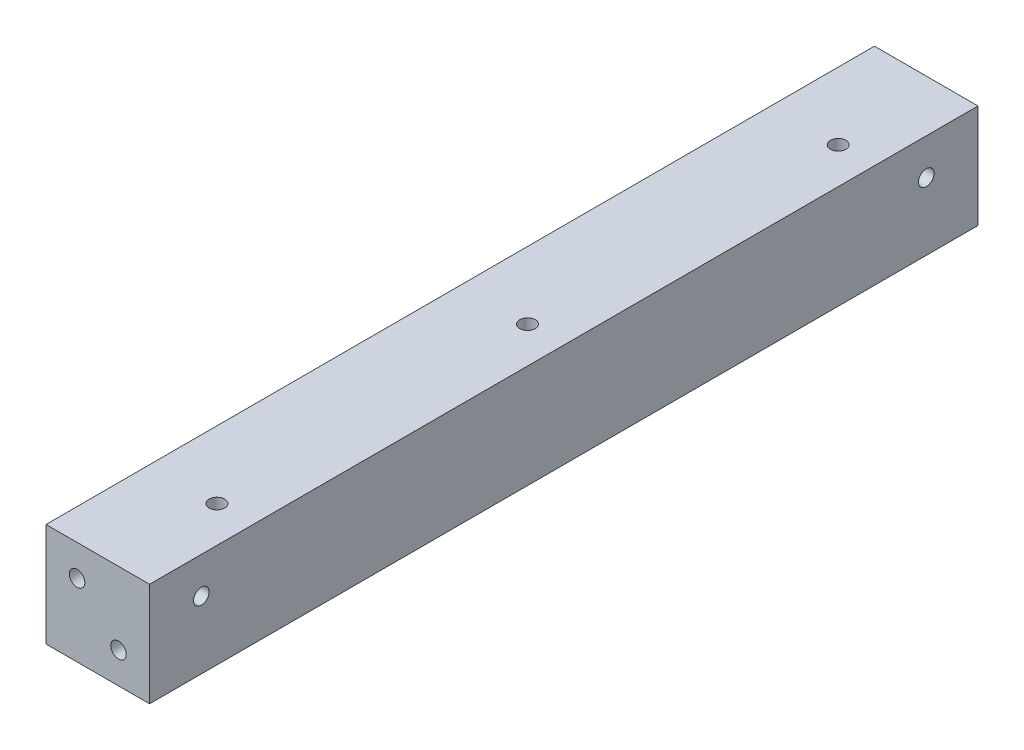
SolidWorks part; units mm, degrees
ref_plane "Ön Düzlem" through (0, 0, 0) normal (0, 0, 1) x (1, 0, 0)
ref_plane "Üst Düzlem" through (0, 0, 0) normal (0, 1, 0) x (1, 0, 0)
ref_plane "Sağ Düzlem" through (0, 0, 0) normal (1, 0, 0) x (0, 0, -1)
sketch "Çizim1" plane through (0, 0, 0) normal (0, 0, 1) x (1, 0, 0)
  line L0 (0, 20) -> (20, 0) construction
  line L1 (0, 0) -> (20, 0)
  line L2 (0, 0) -> (0, 20)
  line L3 (0, 20) -> (20, 20)
  line L4 (20, 0) -> (20, 20)
  line L5 (20, 20) -> (0, 0) construction
  point P4 (10, 10)
extrude "Yükseklik-Ekstrüzyon1" add sketch "Çizim1" along normal blind 160
sketch "Çizim2" plane through (0, 0, 0) normal (-1, 0, 0) x (0, 0, 1)
  line L0 (20, 0) -> (20, 20) construction
  line L1 (160, 0) -> (0, 0) construction
  line L2 (160, 20) -> (0, 20) construction
  line L3 (80, 0) -> (80, 20) construction
  line L4 (140, 0) -> (140, 20) construction
  line L5 (0, 20) -> (0, 0) construction
  line L6 (160, 20) -> (160, 0) construction
  line L7 (0, 7) -> (160, 7) construction
  point P16 (20, 7)
  point P17 (80, 7)
  point P18 (140, 7)
  dimension "D1" = 20
  dimension "D2" = 20
  dimension "D3" = 7
sketch "Çizim4" plane through (0, 20, 0) normal (0, 1, 0) x (1, 0, 0)
  line L0 (13, 0) -> (13, -160) construction
  line L1 (20, 0) -> (0, 0) construction
  line L2 (20, -160) -> (0, -160) construction
  line L3 (20, -160) -> (20, 0) construction
  line L4 (0, -20) -> (20, -20) construction
  line L5 (0, -80) -> (20, -80) construction
  line L6 (0, 0) -> (0, -160) construction
  line L7 (0, -140) -> (20, -140) construction
  point P19 (13, -20)
  point P20 (13, -80)
  point P21 (13, -140)
  dimension "D1" = 7
sketch "Çizim13" plane through (0, 0, 160) normal (0, 0, 1) x (1, 0, 0)
  line L0 (20, 0) -> (20, 20) construction
  line L2 (0, 0) -> (20, 0) construction
  line L4 (0, 0) -> (0, 20) construction
  line L5 (0, 20) -> (20, 20) construction
  circle A0 centre (14, 6) radius 1.5
  circle A1 centre (6, 14) radius 1.5
  dimension "D1" = 6
  dimension "D3" = 6
  dimension "D2" = 6
  dimension "D4" = 6
extrude "Kes-Ekstrüzyon1" cut sketch "Çizim13" against normal blind 10
cosmetic thread "Cosmetic Thread1" parameters "D2"=4
cosmetic thread "Cosmetic Thread14" parameters "D2"=4
sketch "Çizim15" plane through (0, 0, 0) normal (0, 0, -1) x (-1, 0, 0)
  line L0 (-20, 0) -> (-20, 20) construction
  line L2 (0, 0) -> (-20, 0) construction
  line L4 (0, 0) -> (0, 20) construction
  line L5 (0, 20) -> (-20, 20) construction
  circle A0 centre (-14, 6) radius 1.5
  circle A1 centre (-6, 14) radius 1.5
  dimension "D1" = 6
  dimension "D3" = 6
  dimension "D4" = 6
  dimension "D2" = 6
extrude "Kes-Ekstrüzyon2" cut sketch "Çizim15" against normal blind 10
cosmetic thread "Cosmetic Thread2" parameters "D2"=4
cosmetic thread "Cosmetic Thread13" parameters "D2"=4
sketch "Çizim18" plane through (20, 0, 0) normal (1, 0, 0) x (0, 0, -1)
  line L0 (0, 0) -> (0, 20) construction
  line L1 (0, 20) -> (-160, 20) construction
  line L2 (-160, 0) -> (-160, 20) construction
  circle A0 centre (-10, 13) radius 1.5
  circle A1 centre (-150, 13) radius 1.5
  dimension "D1" = 10
  dimension "D2" = 7
  dimension "D3" = 10
  dimension "D4" = 7
extrude "Kes-Ekstrüzyon3" cut sketch "Çizim18" against normal blind 10
cosmetic thread "Cosmetic Thread11" parameters "D2"=4
cosmetic thread "Cosmetic Thread12" parameters "D2"=4
sketch "Çizim20" plane through (0, 0, 0) normal (0, -1, 0) x (1, 0, 0)
  line L0 (0, 0) -> (0, 160) construction
  line L1 (0, 0) -> (20, 0) construction
  line L2 (0, 160) -> (20, 160) construction
  circle A0 centre (7, 10) radius 1.5
  circle A1 centre (7, 150) radius 1.5
  dimension "D1" = 7
  dimension "D2" = 10
  dimension "D3" = 7
  dimension "D4" = 10
extrude "Kes-Ekstrüzyon4" cut sketch "Çizim20" against normal blind 10
cosmetic thread "Cosmetic Thread9" parameters "D2"=4
cosmetic thread "Cosmetic Thread10" parameters "D2"=4
sketch "Sketch1" plane through (0, 20, 0) normal (0, 1, 0) x (1, 0, 0)
  circle A0 centre (13, -20) radius 1.5
  circle A1 centre (13, -80) radius 1.5
  circle A2 centre (13, -140) radius 1.5
extrude "Cut-Extrude1" cut sketch "Sketch1" against normal blind 10
cosmetic thread "Cosmetic Thread6" parameters "D2"=4
cosmetic thread "Cosmetic Thread7" parameters "D2"=4
cosmetic thread "Cosmetic Thread8" parameters "D2"=4
sketch "Sketch2" plane through (0, 0, 0) normal (-1, 0, 0) x (0, 0, 1)
  circle A0 centre (20, 7) radius 1.5
  circle A1 centre (80, 7) radius 1.5
  circle A2 centre (140, 7) radius 1.5
extrude "Cut-Extrude2" cut sketch "Sketch2" against normal blind 10
cosmetic thread "Cosmetic Thread3" parameters "D2"=4
cosmetic thread "Cosmetic Thread4" parameters "D2"=4
cosmetic thread "Cosmetic Thread5" parameters "D2"=4
